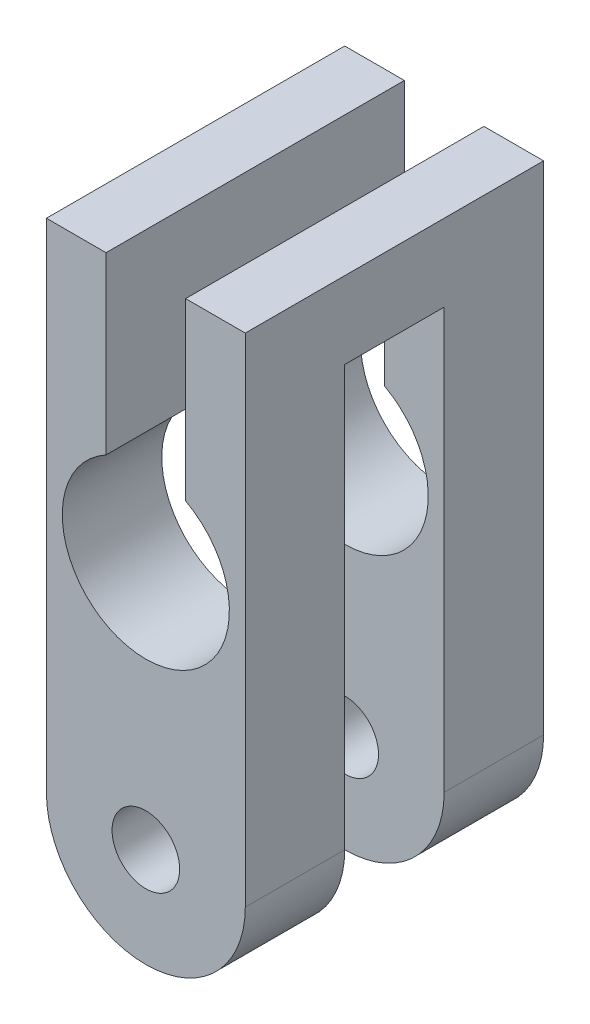
SolidWorks part; units mm, degrees
ref_plane "Front Plane" through (0, 0, 0) normal (1, 0, 0) x (0, 1, 0)
ref_plane "Top Plane" through (0, 0, 0) normal (0, 0, 1) x (0, 1, 0)
ref_plane "Right Plane" through (0, 0, 0) normal (0, 1, 0) x (-1, 0, 0)
ref_plane "Plane3" through (0, 0, 5) normal (0, 0, 1) x (0, 1, 0)
sketch "Sketch1" plane through (0, 0, 0) normal (0, 0, 1) x (0, 1, 0)
  line L9 (0, 0) -> (25, 0)
  line L10 (25, 0) -> (25, 3)
  line L11 (25, 10) -> (0, 10)
  line L12 (25, 7) -> (16.1932, 7)
  line L14 (16.1932, 3) -> (25, 3)
  line L15 (25, 7) -> (25, 10)
  arc A2 (0, 10) -> (0, 0) centre (0, 5) ccw
  circle A3 centre (0, 5) radius 1.7
  arc A4 (16.1932, 7) -> (16.1932, 3) centre (12.5, 5) ccw
  dimension "D1" = 10
  dimension "D2" = 30
  dimension "D3" = 3.4
  dimension "D4" = 8.4
  dimension "D5" = 3
  dimension "D6" = 3
extrude "Boss-Extrude1" add sketch "Sketch1" along normal blind 5 contours A2 L9 L10 L14 A4 L12 L15 L11
sketch "Sketch2" plane through (0, 0, 5) normal (0, 0, 1) x (1, 0, 0)
  circle A0 centre (-5, 0) radius 1.7
  dimension "D1" = 3.4
extrude "Cut-Extrude1" cut sketch "Sketch2" against normal through all
ref_plane "Plane1" through (0, 0, 15) normal (0, 0, 1) x (1, 0, 0)
sketch "Sketch5" plane through (0, 0, 15) normal (0, 0, 1) x (1, 0, 0)
  line L0 (-10, 25) -> (-10, 0) construction
  line L1 (-10, 21) -> (-7, 21)
  line L2 (-10, 21) -> (-10, 25)
  line L3 (-10, 25) -> (-7, 25)
  line L4 (-7, 21) -> (-7, 25)
  line L5 (-3, 16.1932) -> (-3, 25) construction
  line L6 (-3, 21.1307) -> (0, 21.1307)
  line L7 (-3, 21.1307) -> (-3, 25)
  line L8 (-3, 25) -> (0, 25)
  line L9 (0, 21.1307) -> (0, 25)
  dimension "D1" = 4
extrude "Boss-Extrude2" add sketch "Sketch5" against normal blind 10
ref_plane "Plane2" through (0, 0, 7.5) normal (0, 0, 1) x (1, 0, 0)
mirror "Mirror2" about plane through (0, 0, 7.5) normal (0, 0, 1) of "Boss-Extrude1"
sketch "Sketch7" plane through (0, 0, 15) normal (0, 0, 1) x (1, 0, 0)
  circle A0 centre (-5, 0) radius 1.7
extrude "Cut-Extrude2" cut sketch "Sketch7" against normal through all
